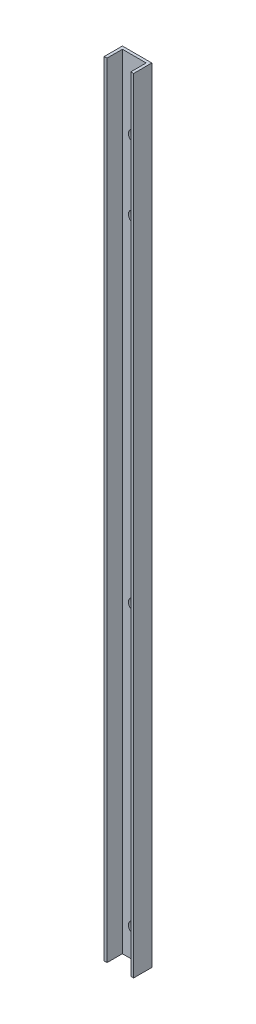
SolidWorks part; units mm, degrees
ref_plane "Front Plane" through (0, 0, 0) normal (0, 0, 1) x (1, 0, 0)
ref_plane "Top Plane" through (0, 0, 0) normal (0, 1, 0) x (1, 0, 0)
ref_plane "Right Plane" through (0, 0, 0) normal (1, 0, 0) x (0, 0, -1)
sketch "Sketch1" plane through (0, 0, 0) normal (0, 1, 0) x (1, 0, 0)
  line L0 (-3.47, -1.8133) -> (-3.47, 4.6867)
  line L1 (-3.47, 4.6867) -> (7.03, 4.6867)
  line L2 (7.03, 4.6867) -> (7.03, -1.8133)
  dimension "D1" = 10.5
  dimension "D2" = 6.5
  dimension "D3" = 6.5
extrude "Extrude-Thin1" add sketch "Sketch1" along normal blind 280 thin
sketch "Sketch2" plane through (0, 0, -4.6867) normal (0, 0, -1) x (-1, 0, 0)
  line L0 (3.47, 280) -> (-7.03, 280) construction
  circle A0 centre (-1.78, 230) radius 2.1
  circle A1 centre (-1.78, 255) radius 2.1
  circle A4 centre (-1.78, 110) radius 2.1
  circle A5 centre (-1.78, 10) radius 2.1
  dimension "D1" = 4.2
  dimension "D2" = 4.2
  dimension "D3" = 50
extrude "Cut-Extrude1" cut sketch "Sketch2" against normal blind 10
